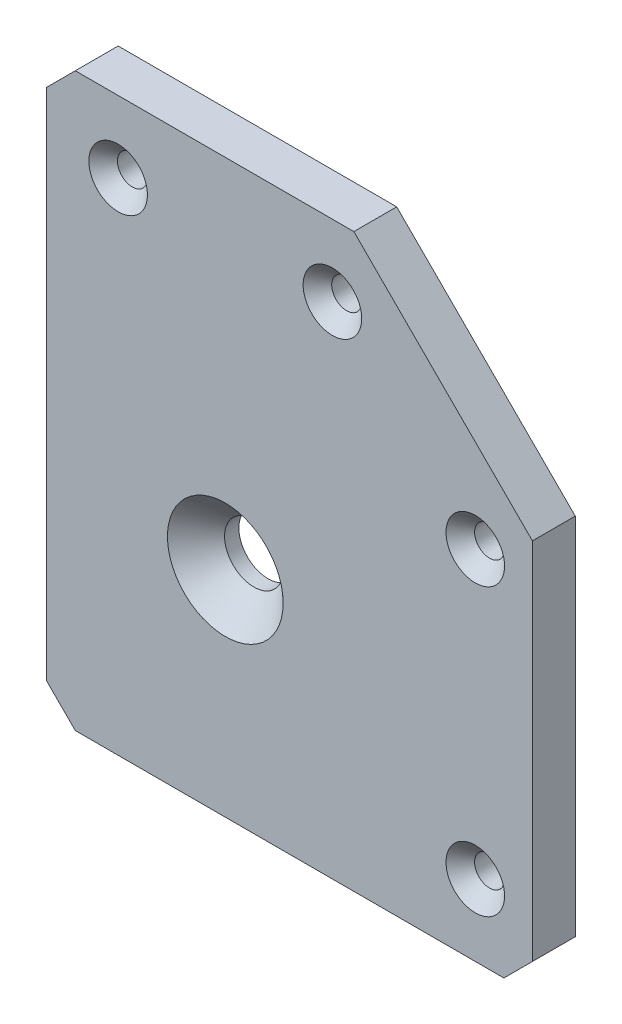
SolidWorks part; units mm, degrees
ref_plane "前视基准面" through (0, 0, 0) normal (0, 0, 1) x (1, 0, 0)
ref_plane "上视基准面" through (0, 0, 0) normal (0, 1, 0) x (1, 0, 0)
ref_plane "右视基准面" through (0, 0, 0) normal (1, 0, 0) x (0, 0, -1)
sketch "草图1" plane through (0, 0, 0) normal (0, 0, 1) x (1, 0, 0)
  line L0 (35, 20) -> (35, -20) construction
  line L1 (43, -30) -> (-25, -30)
  line L2 (43, -30) -> (43, 50)
  line L3 (43, 50) -> (-25, 50)
  line L4 (-25, -30) -> (-25, 50)
  line L5 (43, -30) -> (-25, 50) construction
  line L6 (43, 50) -> (-25, -30) construction
  line L7 (-15, 40) -> (15, 40) construction
  circle A0 centre (0, 0) radius 4.1
  circle A1 centre (35, 20) radius 2.1
  circle A2 centre (35, -20) radius 2.1
  circle A3 centre (-15, 40) radius 2.1
  circle A4 centre (15, 40) radius 2.1
  point P3 (9, 10)
  point P12 (35, 0)
  point P17 (0, 40)
  point P18 (9, 50)
  dimension "D1" = 50
  dimension "D2" = 8.2
  dimension "D3" = 4.2
  dimension "D6" = 25
  dimension "D8" = 10
  dimension "D9" = 10
  dimension "D4" = 40
  dimension "D5" = 35
  dimension "D7" = 8
  dimension "D10" = 10
extrude "凸台-拉伸1" add sketch "草图1" along normal mid plane 6
chamfer "倒角1" distance 25 angle 45 1 edges at (43, 50, 0)
chamfer "倒角2" distance 4 angle 45 4 edges at (-25, 50, 0) (43, -30, 0) (-25, -30, 0) (4.1, 0, 3)
chamfer "倒角3" distance 2 angle 45 4 edges at (37.1, -20, 3) (37.1, 20, 3) (-12.9, 40, 3) (17.1, 40, 3)
